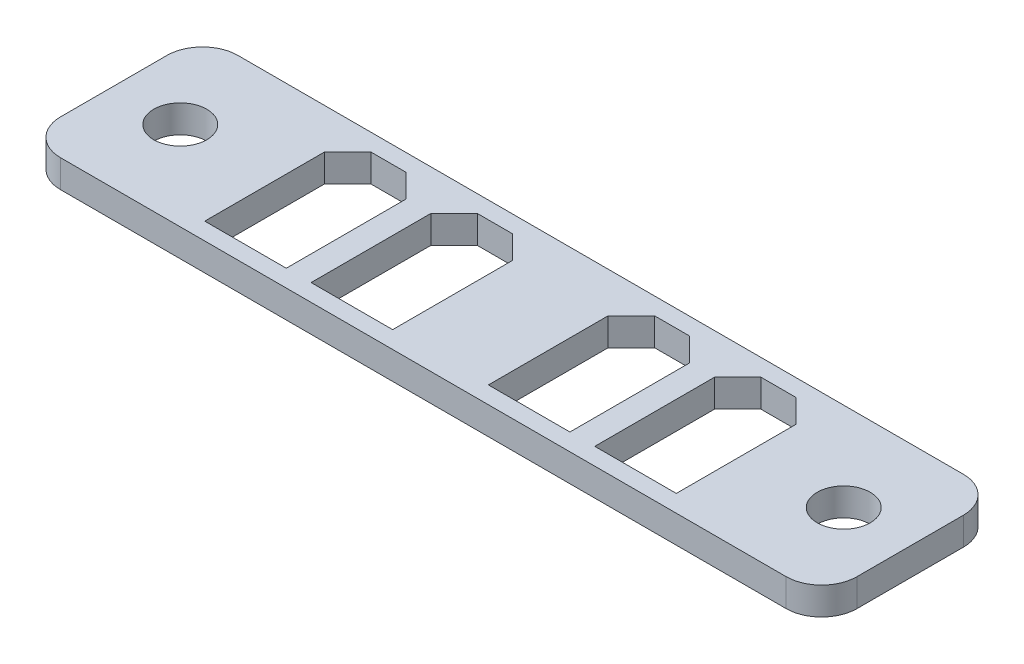
SolidWorks part; units mm, degrees
ref_plane "Front Plane" through (0, 0, 0) normal (0, 0, 1) x (1, 0, 0)
ref_plane "Top Plane" through (0, 0, 0) normal (0, 1, 0) x (1, 0, 0)
ref_plane "Right Plane" through (0, 0, 0) normal (1, 0, 0) x (0, 0, -1)
sketch "Sketch1" plane through (0, 0, 0) normal (0, 1, 0) x (1, 0, 0)
  line L1 (0, 0) -> (57.05, 0)
  line L2 (0, 0) -> (0, 12.7)
  line L3 (0, 12.7) -> (57.05, 12.7)
  line L4 (57.05, 0) -> (57.05, 12.7)
  line L5 (4.7625, 6.35) -> (52.2875, 6.35) construction
  circle A0 centre (52.2875, 6.35) radius 1.8986
  circle A1 centre (4.7625, 6.35) radius 1.8986
  point P9 (28.525, 6.35)
  point P10 (28.525, 0)
  point P11 (0, 6.35)
  dimension "D3" = 3.7973
  dimension "D1" = 12.7
  dimension "D2" = 57.05
  dimension "D4" = 47.525
extrude "Boss-Extrude1" add sketch "Sketch1" along normal blind 1.9844
sketch "Sketch2" plane through (0, 1.9844, 0) normal (0, 1, 0) x (1, 0, 0)
  line L0 (28.525, 12.7) -> (28.525, 0) construction
  line L1 (57.05, 12.7) -> (0, 12.7) construction
  line L2 (0, 0) -> (57.05, 0) construction
  line L3 (14.555, 11.45) -> (14.555, 1.25) construction
  line L4 (22.175, 11.45) -> (22.175, 1.25) construction
  line L5 (34.875, 11.45) -> (34.875, 1.25) construction
  line L6 (0, 6.35) -> (57.05, 6.35) construction
  line L7 (0, 12.7) -> (0, 0) construction
  line L8 (57.05, 0) -> (57.05, 12.7) construction
  line L9 (42.495, 11.47) -> (42.495, 1.23) construction
  point P18 (22.175, 6.35)
  point P19 (34.875, 6.35)
  point P20 (14.555, 6.35)
  point P23 (42.495, 6.35)
  line B0 (17.455, 9.8004) -> (17.455, 1.25) construction
  line B1 (17.475, 1.23) -> (11.635, 1.23)
  line B2 (11.635, 1.23) -> (11.635, 9.8087)
  line B3 (11.635, 9.8087) -> (13.2967, 11.47)
  line B4 (13.2967, 11.47) -> (15.8133, 11.47)
  line B5 (15.8133, 11.47) -> (17.475, 9.8087)
  line B6 (17.475, 9.8087) -> (17.475, 1.23)
  line B7 (39.595, 1.25) -> (39.595, 9.8004) construction
  line B8 (45.415, 1.23) -> (39.575, 1.23)
  line B9 (39.575, 1.23) -> (39.575, 9.8087)
  line B10 (39.575, 9.8087) -> (41.2367, 11.47)
  line B11 (41.2367, 11.47) -> (43.7533, 11.47)
  line B12 (43.7533, 11.47) -> (45.415, 9.8087)
  line B13 (45.415, 9.8087) -> (45.415, 1.23)
  line B14 (19.275, 1.25) -> (19.275, 9.8004) construction
  line B15 (25.095, 1.23) -> (19.255, 1.23)
  line B16 (19.255, 1.23) -> (19.255, 9.8087)
  line B17 (19.255, 9.8087) -> (20.9167, 11.47)
  line B18 (20.9167, 11.47) -> (23.4333, 11.47)
  line B19 (23.4333, 11.47) -> (25.095, 9.8087)
  line B20 (25.095, 9.8087) -> (25.095, 1.23)
  line B21 (37.775, 9.8004) -> (37.775, 1.25) construction
  line B22 (37.795, 1.23) -> (31.955, 1.23)
  line B23 (31.955, 1.23) -> (31.955, 9.8087)
  line B24 (31.955, 9.8087) -> (33.6167, 11.47)
  line B25 (33.6167, 11.47) -> (36.1333, 11.47)
  line B26 (36.1333, 11.47) -> (37.795, 9.8087)
  line B27 (37.795, 9.8087) -> (37.795, 1.23)
  dimension "D1" = 6.35
  dimension "D2" = 6.35
  dimension "D3" = 13.97
  dimension "D4" = 13.97
sketch_block_instance "IRsensormounting-1"
sketch_block "IRsensormounting"
sketch_block_instance "IRsensormounting-2"
sketch_block_instance "IRsensormounting-3"
sketch_block_instance "IRsensormounting-4"
extrude "Cut-Extrude1" cut sketch "Sketch2" against normal up to next
fillet "Fillet1" radius 2.54 4 edges at (0, 0.9922, 0) (0, 0.9922, -12.7) (57.05, 0.9922, 0) (57.05, 0.9922, -12.7)
